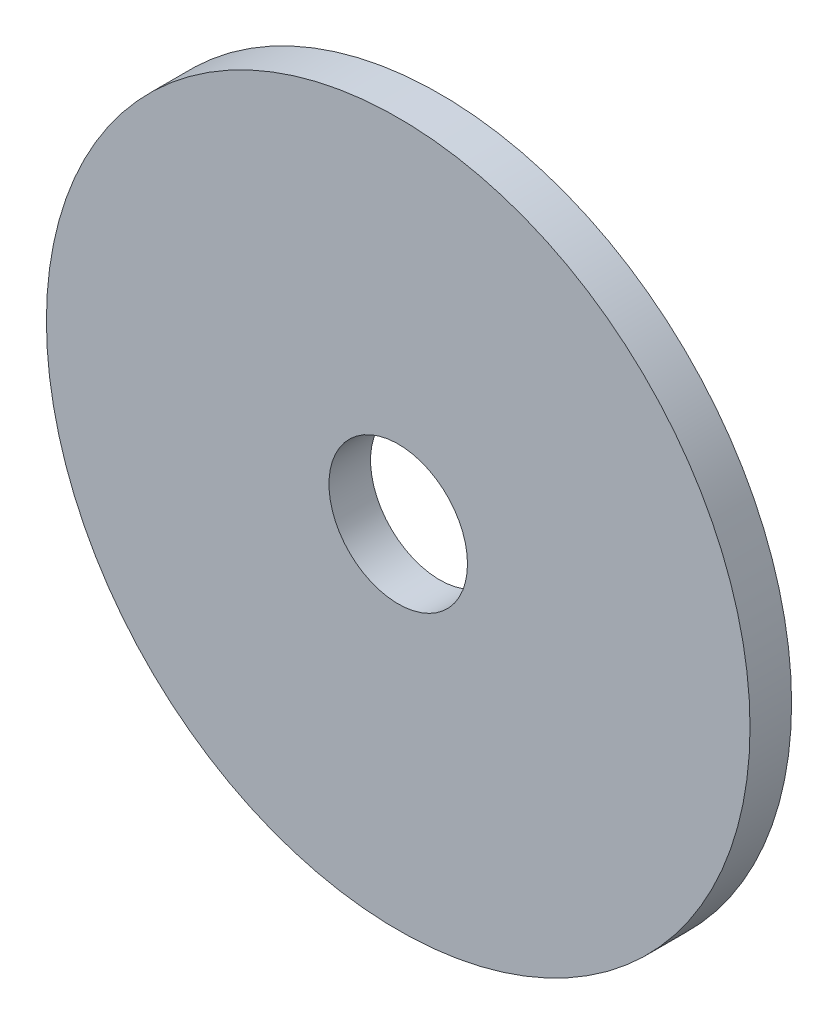
SolidWorks part; units mm, degrees
ref_plane "Front Plane" through (0, 0, 0) normal (0, 0, 1) x (1, 0, 0)
ref_plane "Top Plane" through (0, 0, 0) normal (0, 1, 0) x (1, 0, 0)
ref_plane "Right Plane" through (0, 0, 0) normal (1, 0, 0) x (0, 0, -1)
sketch "Sketch1" plane through (0, 0, 0) normal (0, 0, 1) x (1, 0, 0)
  circle A0 centre (0, 0) radius 12.7
  circle A1 centre (0, 0) radius 2.5
  dimension "D1" = 25.4
  dimension "D2" = 5
extrude "Boss-Extrude1" add sketch "Sketch1" along normal blind 1.5
